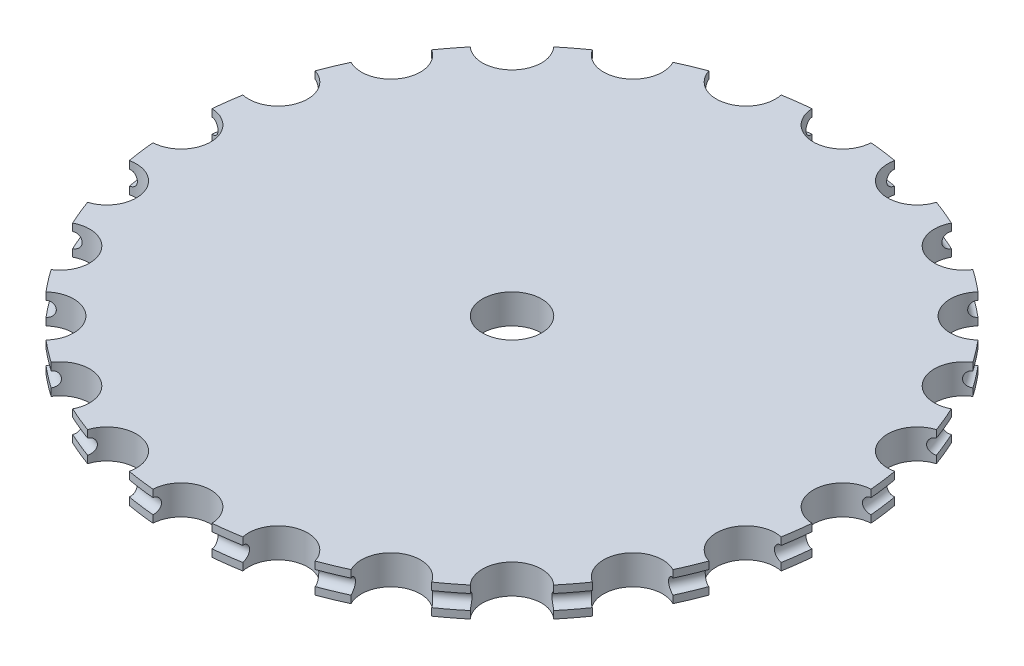
SolidWorks part; units mm, degrees
ref_plane "Front Plane" through (0, 0, 0) normal (0, 0, 1) x (1, 0, 0)
ref_plane "Top Plane" through (0, 0, 0) normal (0, 1, 0) x (1, 0, 0)
ref_plane "Right Plane" through (0, 0, 0) normal (1, 0, 0) x (0, 0, -1)
sketch "Sketch3" plane through (0, 0, 0) normal (0, 0, 1) x (1, 0, 0)
  line L0 (0, 1.5875) -> (0, -1.5875)
  line L1 (0, -1.5875) -> (35.56, -1.5875)
  line L2 (35.56, -1.5875) -> (35.56, -0.7937)
  line L3 (0, 1.5875) -> (35.56, 1.5875)
  line L4 (35.56, 1.5875) -> (35.56, 0.7937)
  arc A0 (35.56, 0.7937) -> (35.56, -0.7937) centre (35.56, 0) ccw
  point P5 (0, 0)
  dimension "D2" = 0.7937
  dimension "D1" = 3.175
  dimension "D3" = 35.56
revolve "Revolve1" add sketch "Sketch3" angle 360 about L0
sketch "Sketch4" plane through (0, 1.5875, 0) normal (0, 1, 0) x (1, 0, 0)
  circle A0 centre (0, 35.56) radius 3.175
  circle A1 centre (0, 0) radius 35.56 construction
  dimension "D1" = 6.35
extrude "Cut-Extrude2" cut sketch "Sketch4" against normal blind 3.175
pattern_circular "CirPattern1" count 24 every 15 about axis through (0, 0, 0) along (0, 1, 0) of "Cut-Extrude2"
sketch "Sketch5" plane through (0, 1.5875, 0) normal (0, 1, 0) x (1, 0, 0)
  circle A0 centre (0, 0) radius 3.175
  dimension "D1" = 6.35
extrude "Cut-Extrude3" cut sketch "Sketch5" against normal through all
